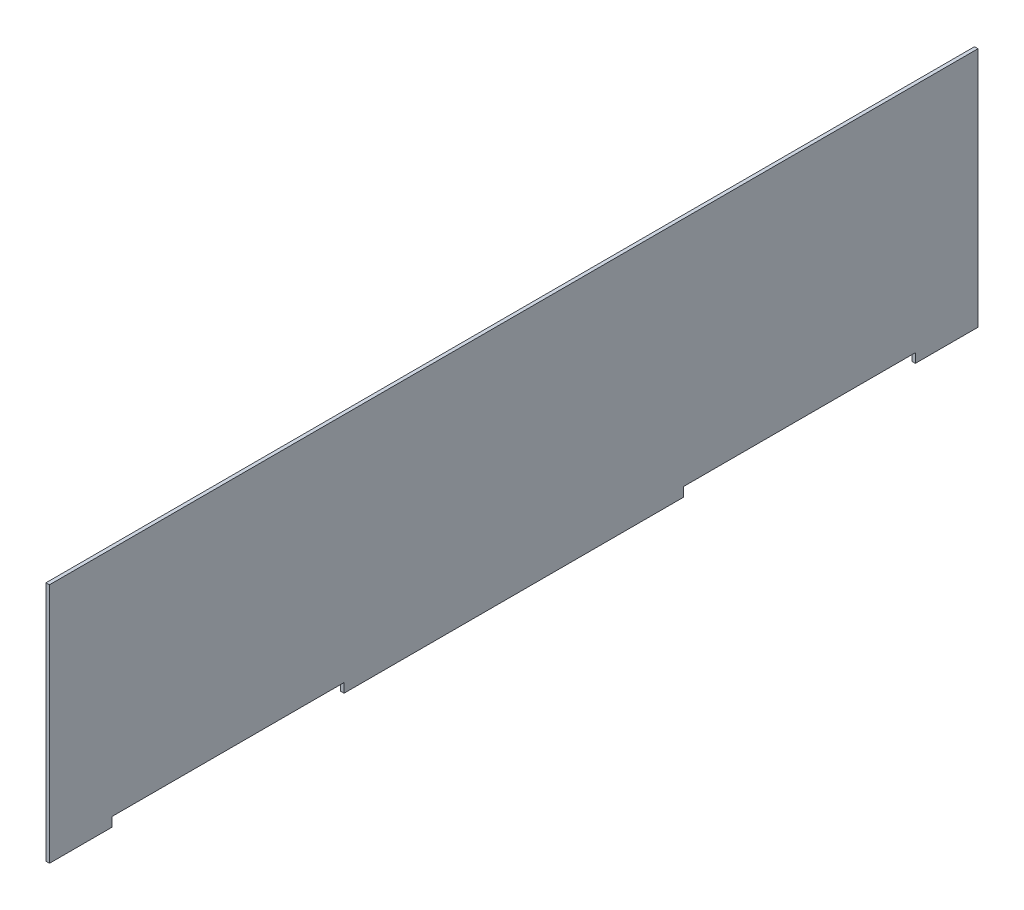
SolidWorks part; units mm, degrees
ref_plane "Front Plane" through (0, 0, 0) normal (0, 0, 1) x (1, 0, 0)
ref_plane "Top Plane" through (0, 0, 0) normal (0, 1, 0) x (1, 0, 0)
ref_plane "Right Plane" through (0, 0, 0) normal (1, 0, 0) x (0, 0, -1)
sketch "Sketch1" plane through (0, 0, 0) normal (1, 0, 0) x (0, 0, -1)
  line L0 (-4991.9853, -1296.9435) -> (-4451.9853, -1296.9435)
  line L1 (-4991.9853, 783.0565) -> (3014.0147, 783.0565)
  line L2 (-4991.9853, 783.0565) -> (-4991.9853, -1296.9435)
  line L5 (-4991.9853, 783.0565) -> (0, 0) construction
  line L6 (-4991.9853, -1296.9435) -> (-2451.9853, -637.0384) construction
  line L7 (-4451.9853, -1296.9435) -> (-4451.9853, -1216.9435)
  line L8 (-4451.9853, -1216.9435) -> (-2451.9853, -1216.9435)
  line L15 (0, 0) -> (3014.0147, 783.0565) construction
  line L16 (-2451.9853, -1216.9435) -> (-2451.9853, -1296.9435)
  line L17 (-2451.9853, -1296.9435) -> (474.0147, -1296.9435)
  line L18 (474.0147, -1296.9435) -> (474.0147, -1216.9435)
  line L19 (474.0147, -1216.9435) -> (2474.0147, -1216.9435)
  line L20 (2474.0147, -1216.9435) -> (2474.0147, -1296.9435)
  line L21 (2474.0147, -1296.9435) -> (3014.0147, -1296.9435)
  line L22 (3014.0147, -1296.9435) -> (3014.0147, 783.0565)
  point P0 (0, 0)
  dimension "D1" = 2080
  dimension "D2" = 8006
  dimension "D3" = 540
  dimension "D4" = 80
  dimension "D5" = 540
  dimension "D6" = 2000
  dimension "D7" = 2000
extrude "Boss-Extrude1" add sketch "Sketch1" along normal blind 30
